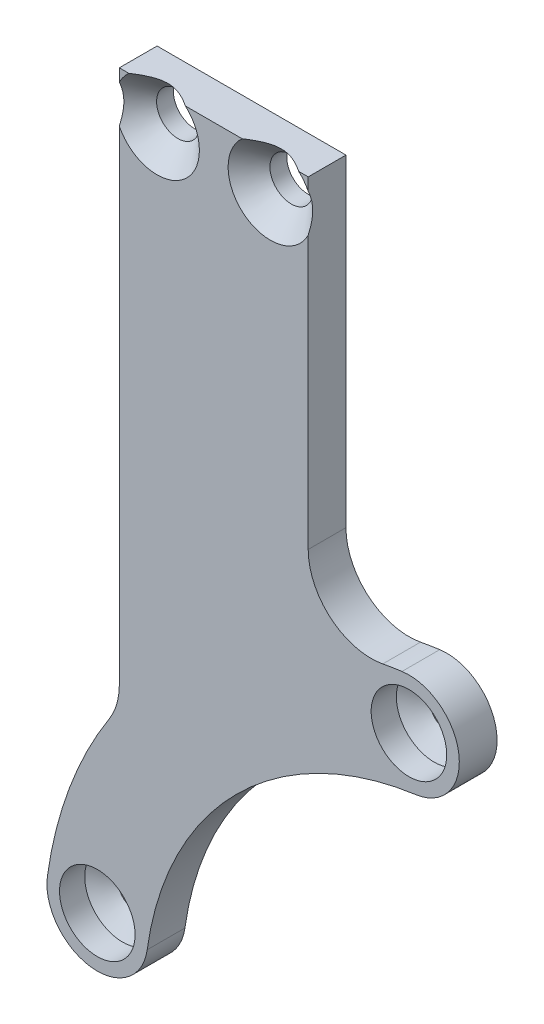
SolidWorks part; units mm, degrees
ref_plane "Plano frontal" through (0, 0, 0) normal (0, 0, 1) x (1, 0, 0)
ref_plane "Plano superior" through (0, 0, 0) normal (0, 1, 0) x (1, 0, 0)
ref_plane "Plano direito" through (0, 0, 0) normal (1, 0, 0) x (0, 0, -1)
sketch "Esboço1" plane through (0, 0, 0) normal (0, 0, 1) x (1, 0, 0)
  line L0 (-2.7413, 0) -> (1.7356, 0) construction
  line L2 (0, 0.5872) -> (0, 6.5453) construction
  line L9 (-12, 30.7684) -> (-12, 63)
  line L10 (-12, 63) -> (-27, 63)
  line L11 (-27, 63) -> (-27, 19.0183)
  line L12 (-32.7106, 4.5512) -> (0, 0) construction
  line L13 (0, 0) -> (-4.5512, 32.7106) construction
  arc A6 (-27, 19.0183) -> (-32.7106, 4.5512) centre (0, 0) ccw
  arc A7 (-12, 30.7684) -> (-4.5512, 32.7106) centre (0, 0) cw
  arc A8 (-24.7869, 3.4488) -> (-3.4488, 24.7869) centre (0, 0) cw
  arc A9 (-24.7869, 3.4488) -> (-32.7106, 4.5512) centre (-28.7487, 4) cw
  arc A10 (-3.4488, 24.7869) -> (-4.5512, 32.7106) centre (-4, 28.7487) ccw
  point P7 (0, 0)
  point P8 (0, 0)
  point P11 (0, 0)
  dimension "D2" = 15
  dimension "D1" = 4
  dimension "D3" = 4
  dimension "D4" = 35
  dimension "D6" = 63
  dimension "D7" = 27
extrude "Ressalto-extrusão2" add sketch "Esboço1" along normal blind 3
hole_wizard "Broca de rosquear para tarraxa de M2.51" positions "Esboço2" profile "Esboço3" hole size "M2.5" standard "ISO" end condition up to next
sketch "Esboço2" plane through (0, 0, 3) normal (0, 0, 1) x (1, 0, 0)
  point P18 (-28.7487, 4)
  point P21 (-4, 28.7487)
sketch "Esboço3" plane through (-28.7487, 4, 3) normal (1, 0, 0) x (0, -1, 0)
  line L0 (0, 0) -> (0, 3)
  line L1 (0, 3) -> (1.025, 3)
  line L2 (1.025, 3) -> (1.025, 0)
  line L5 (1.025, 0) -> (0, 0)
  line L11 (0, -6.35) -> (0, 107.95) construction
  dimension "Thru Hole Dia." = 2.05
  dimension "Thru Hole Depth" = 3
hole_wizard "Furo de diâmetro Ø6.0 (6)2" positions "Esboço8" profile "Esboço10" hole size "Ø6.0" standard "ISO"
sketch "Esboço8" plane through (0, 0, 3) normal (0, 0, 1) x (1, 0, 0)
  point P15 (-28.7487, 4)
  point P18 (-4, 28.7487)
sketch "Esboço10" plane through (-28.7487, 4, 3) normal (1, 0, 0) x (0, -1, 0)
  line L0 (0, 0) -> (0, 3.8026)
  line L1 (0, 3.8026) -> (3, 2)
  line L2 (3, 2) -> (3, 0)
  line L5 (3, 0) -> (0, 0)
  line L10 (0, 3.8026) -> (-3, 2) construction
  line L11 (0, -6.35) -> (0, 107.95) construction
  dimension "Hole Dia." = 6
  dimension "Hole Depth" = 2
  dimension "Drill Angle" = 118
hole_wizard "Escareado para SFHCS M31" positions "Esboço11" profile "Esboço13" countersink size "M3" standard "Ansi Metric" end condition through all
sketch "Esboço11" plane through (0, 0, 3) normal (0, 0, 1) x (1, 0, 0)
  line L3 (-12, 63) -> (-27, 63) construction
  line L4 (-27, 63) -> (-27, 19.0183) construction
  line L5 (-12, 30.7684) -> (-12, 63) construction
  point P0 (-24, 60.5)
  point P2 (-15, 60.5)
  dimension "D1" = 2.5
  dimension "D2" = 2.5
  dimension "D3" = 3
  dimension "D4" = 3
sketch "Esboço13" plane through (-24, 60.5, 3) normal (1, 0, 0) x (0, -1, 0)
  line L0 (0, 0) -> (0, 3)
  line L1 (0, 3) -> (1.7, 3)
  line L2 (1.7, 3) -> (1.7, 1.66)
  line L3 (1.7, 1.66) -> (3.36, 0)
  line L5 (3.36, 0) -> (0, 0)
  line L6 (-1.7, 1.66) -> (-3.36, 0) construction
  line L11 (0, -6.35) -> (0, 107.95) construction
  dimension "Thru Hole Dia." = 3.4
  dimension "Thru Hole Depth" = 3
  dimension "Near C'Sink Dia." = 6.72
  dimension "Near C'Sink Angle" = 90
fillet "Filete1" radius 5 2 edges at (-27, 19.0183, 1.5) (-12, 30.7684, 1.5)
